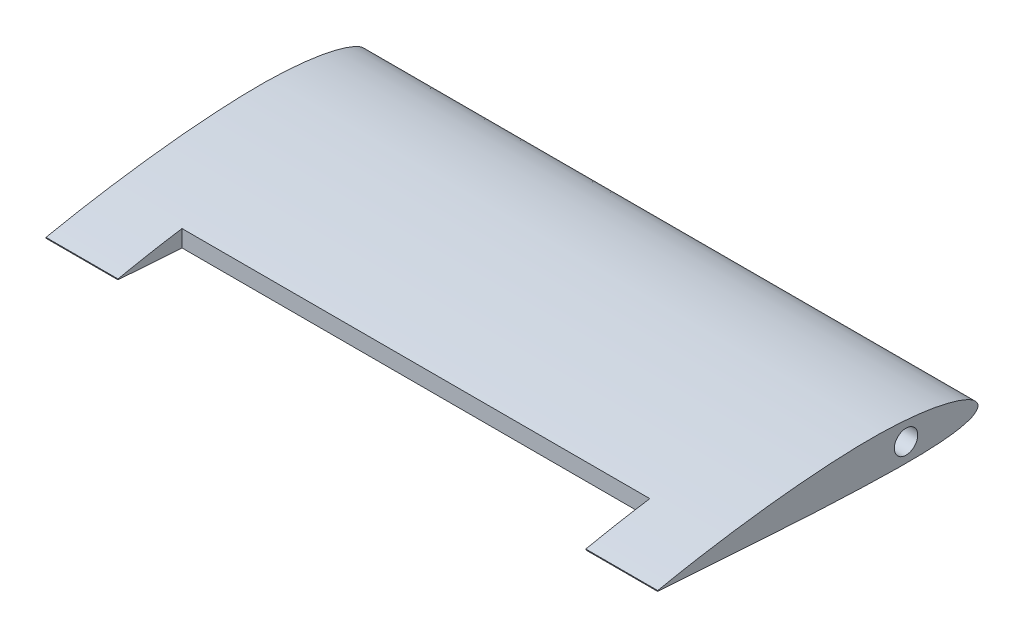
SolidWorks part; units mm, degrees
ref_plane "Front Plane" through (0, 0, 0) normal (0, 0, 1) x (1, 0, 0)
ref_plane "Top Plane" through (0, 0, 0) normal (0, 1, 0) x (1, 0, 0)
ref_plane "Right Plane" through (0, 0, 0) normal (1, 0, 0) x (0, 0, -1)
sketch "Sketch4" plane through (0, 0, 0) normal (0, 0, 1) x (1, 0, 0)
  line L0 (-30.3109, 17.5) -> (30.3109, 17.5)
  arc A1 (30.3109, 17.5) -> (-30.3109, 17.5) centre (0, 0) ccw
  dimension "D1" = 35
  dimension "D2" = 17.5
extrude "Exterior" add sketch "Sketch4" along normal blind 89 contours L0 A1
sketch "Sketch5" plane through (0, 0, 0) normal (0, 0, -1) x (-1, 0, 0)
  line L0 (30.3109, 17.5) -> (-30.3109, 17.5) construction
  line L1 (23.1247, 17.5) -> (-23.1247, 17.5)
  arc A0 (23.1247, 17.5) -> (-23.1247, 17.5) centre (0, 0) ccw
  dimension "D1" = 58
extrude "Boss-Extrude1" add sketch "Sketch5" along normal blind 15
curve "Curve3"
  spline degree 3 poles (0, 1.3, 1000) (0, 4.7133, 983.3426) (0, 11.531, 950.0715) (0, 24.0186, 883.4722) (0, 37.8548, 800.1781) (0, 52.175, 700.1592) (0, 64.1175, 600.1567) (0, 72.8619, 500.1109) (0, 78.7837, 400.0878) (0, 79.786, 316.6355) (0, 77.0249, 249.9395) (0, 72.979, 199.8766) (0, 66.5721, 149.7505) (0, 58.6825, 108.0331) (0, 49.7566, 74.7751) (0, 41.6416, 49.5609) (0, 32.1864, 28.1982) (0, 20.723, 9.771) (0, 0.8988, -6.2982) (0, -16.5264, 10.3934) (0, -24.4739, 28.476) (0, -30.5108, 49.7447) (0, -34.8393, 74.8759) (0, -38.5332, 108.2669) (0, -41.3764, 149.947) (0, -42.5163, 199.9941) (0, -42.3574, 250.0055) (0, -40.8857, 316.6783) (0, -38.2375, 400.0272) (0, -33.6287, 500.0334) (0, -27.6385, 600.0106) (0, -21.4122, 700.0048) (0, -15.1098, 800.0161) (0, -9.3053, 883.3314) (0, -4.8282, 950.0042) (0, -2.4761, 983.334) (0, -1.3, 1000) knots 0 0 0 0 0.025012 0.049959 0.099673 0.149206 0.198581 0.247805 0.296917 0.345953 0.370492 0.395091 0.419815 0.444799 0.45749 0.470406 0.483879 0.491264 0.503459 0.513609 0.520451 0.533235 0.545691 0.558032 0.582609 0.607135 0.631652 0.656174 0.705234 0.75432 0.803437 0.852566 0.901701 0.950849 0.975423 1 1 1 1
sketch "Sketch7" plane through (0, 0, 0) normal (1, 0, 0) x (0, 0, -1)
  line L0 (-89, 21.3887) -> (-89, 21.1573)
  line L1 (-89, 21.273) -> (0, 21.3903) construction
  line L2 (0, 21.3903) -> (-0.0573, 64.8516) construction
  line L7 (-89, 17.5) -> (0, 17.5) construction
  line L9 (0, 17.5) -> (0, 29) construction
  spline S1 degree 3 poles (-89, 21.3887) (-87.5176, 21.6924) (-84.5567, 22.2992) (-78.6297, 23.4105) (-71.2171, 24.6418) (-62.316, 25.9162) (-53.4164, 26.979) (-44.5129, 27.7573) (-35.6114, 28.2842) (-28.1847, 28.3735) (-22.2492, 28.1277) (-17.7939, 27.7677) (-13.3329, 27.1975) (-9.6203, 26.4954) (-6.6606, 25.701) (-4.4167, 24.9788) (-2.5155, 24.1374) (-0.8756, 23.1172) (0.5545, 21.353) (-0.931, 19.8022) (-2.5402, 19.095) (-4.433, 18.5577) (-6.6696, 18.1725) (-9.6412, 17.8438) (-13.3504, 17.5907) (-17.8043, 17.4893) (-22.255, 17.5034) (-28.1885, 17.6344) (-35.606, 17.8701) (-44.506, 18.2802) (-53.4034, 18.8133) (-62.3022, 19.3674) (-71.2026, 19.9283) (-78.6172, 20.4449) (-84.5507, 20.8433) (-87.5168, 21.0526) (-89, 21.1573) knots 0 0 0 0 0.025012 0.049959 0.099673 0.149206 0.198581 0.247805 0.296917 0.345953 0.370492 0.395091 0.419815 0.444799 0.45749 0.470406 0.483879 0.491264 0.503459 0.513609 0.520451 0.533235 0.545691 0.558032 0.582609 0.607135 0.631652 0.656174 0.705234 0.75432 0.803437 0.852566 0.901701 0.950849 0.975423 1 1 1 1
  dimension "D1" = 89
ref_plane "Plane1" through (80, 0, 0) normal (1, 0, 0) x (0, 0, -1)
ref_plane "Plane2" through (-80, 0, 0) normal (1, 0, 0) x (0, 0, -1)
sketch "Sketch8" plane through (80, 0, 0) normal (1, 0, 0) x (0, 0, -1)
  line L0 (-89, 21.3887) -> (-89, 21.1573)
  spline S0 degree 3 poles (-469.3669, 946.2185) (-209.3584, -26.81) (-147.9272, 10.417) (-78.6297, 23.4105) (-71.2171, 24.6418) (-62.316, 25.9162) (-53.4164, 26.979) (-44.5129, 27.7573) (-35.6114, 28.2842) (-28.1847, 28.3735) (-22.2492, 28.1277) (-17.7939, 27.7677) (-13.3329, 27.1975) (-9.6203, 26.4954) (-6.6606, 25.701) (-4.4167, 24.9788) (-2.5155, 24.1374) (-0.8756, 23.1172) (0.5545, 21.353) (-0.931, 19.8022) (-2.5402, 19.095) (-4.433, 18.5577) (-6.6696, 18.1725) (-9.6412, 17.8438) (-13.3504, 17.5907) (-17.8043, 17.4893) (-22.255, 17.5034) (-28.1885, 17.6344) (-35.606, 17.8701) (-44.506, 18.2802) (-53.4034, 18.8133) (-62.3022, 19.3674) (-71.2026, 19.9283) (-78.6172, 20.4449) (-191.4759, 28.0234) (-300.415, 49.2551) (-474.7288, -901.4445) knots -1.065698 -1.065698 -1.065698 -1.065698 0.025012 0.049959 0.099673 0.149206 0.198581 0.247805 0.296917 0.345953 0.370492 0.395091 0.419815 0.444799 0.45749 0.470406 0.483879 0.491264 0.503459 0.513609 0.520451 0.533235 0.545691 0.558032 0.582609 0.607135 0.631652 0.656174 0.705234 0.75432 0.803437 0.852566 0.901701 0.950849 0.975423 2.771414 2.771414 2.771414 2.771414 only from (-89, 21.3887) to (-89, 21.1573) construction
  spline S1 degree 3 poles (-89, 21.3887) (-87.5176, 21.6924) (-84.5567, 22.2992) (-78.6297, 23.4105) (-71.2171, 24.6418) (-62.316, 25.9162) (-53.4164, 26.979) (-44.5129, 27.7573) (-35.6114, 28.2842) (-28.1847, 28.3735) (-22.2492, 28.1277) (-17.7939, 27.7677) (-13.3329, 27.1975) (-9.6203, 26.4954) (-6.6606, 25.701) (-4.4167, 24.9788) (-2.5155, 24.1374) (-0.8756, 23.1172) (0.5545, 21.353) (-0.931, 19.8022) (-2.5402, 19.095) (-4.433, 18.5577) (-6.6696, 18.1725) (-9.6412, 17.8438) (-13.3504, 17.5907) (-17.8043, 17.4893) (-22.255, 17.5034) (-28.1885, 17.6344) (-35.606, 17.8701) (-44.506, 18.2802) (-53.4034, 18.8133) (-62.3022, 19.3674) (-71.2026, 19.9283) (-78.6172, 20.4449) (-84.5507, 20.8433) (-87.5168, 21.0526) (-89, 21.1573) knots 0 0 0 0 0.025012 0.049959 0.099673 0.149206 0.198581 0.247805 0.296917 0.345953 0.370492 0.395091 0.419815 0.444799 0.45749 0.470406 0.483879 0.491264 0.503459 0.513609 0.520451 0.533235 0.545691 0.558032 0.582609 0.607135 0.631652 0.656174 0.705234 0.75432 0.803437 0.852566 0.901701 0.950849 0.975423 1 1 1 1
sketch "Sketch9" plane through (-80, 0, 0) normal (1, 0, 0) x (0, 0, -1)
  line L0 (-89, 21.3887) -> (-89, 21.1573)
  spline S0 degree 3 poles (-469.3669, 946.2185) (-209.3584, -26.81) (-147.9272, 10.417) (-78.6297, 23.4105) (-71.2171, 24.6418) (-62.316, 25.9162) (-53.4164, 26.979) (-44.5129, 27.7573) (-35.6114, 28.2842) (-28.1847, 28.3735) (-22.2492, 28.1277) (-17.7939, 27.7677) (-13.3329, 27.1975) (-9.6203, 26.4954) (-6.6606, 25.701) (-4.4167, 24.9788) (-2.5155, 24.1374) (-0.8756, 23.1172) (0.5545, 21.353) (-0.931, 19.8022) (-2.5402, 19.095) (-4.433, 18.5577) (-6.6696, 18.1725) (-9.6412, 17.8438) (-13.3504, 17.5907) (-17.8043, 17.4893) (-22.255, 17.5034) (-28.1885, 17.6344) (-35.606, 17.8701) (-44.506, 18.2802) (-53.4034, 18.8133) (-62.3022, 19.3674) (-71.2026, 19.9283) (-78.6172, 20.4449) (-191.4759, 28.0234) (-300.415, 49.2551) (-474.7288, -901.4445) knots -1.065698 -1.065698 -1.065698 -1.065698 0.025012 0.049959 0.099673 0.149206 0.198581 0.247805 0.296917 0.345953 0.370492 0.395091 0.419815 0.444799 0.45749 0.470406 0.483879 0.491264 0.503459 0.513609 0.520451 0.533235 0.545691 0.558032 0.582609 0.607135 0.631652 0.656174 0.705234 0.75432 0.803437 0.852566 0.901701 0.950849 0.975423 2.771414 2.771414 2.771414 2.771414 only from (-89, 21.3887) to (-89, 21.1573) construction
  spline S1 degree 3 poles (-89, 21.3887) (-87.5176, 21.6924) (-84.5567, 22.2992) (-78.6297, 23.4105) (-71.2171, 24.6418) (-62.316, 25.9162) (-53.4164, 26.979) (-44.5129, 27.7573) (-35.6114, 28.2842) (-28.1847, 28.3735) (-22.2492, 28.1277) (-17.7939, 27.7677) (-13.3329, 27.1975) (-9.6203, 26.4954) (-6.6606, 25.701) (-4.4167, 24.9788) (-2.5155, 24.1374) (-0.8756, 23.1172) (0.5545, 21.353) (-0.931, 19.8022) (-2.5402, 19.095) (-4.433, 18.5577) (-6.6696, 18.1725) (-9.6412, 17.8438) (-13.3504, 17.5907) (-17.8043, 17.4893) (-22.255, 17.5034) (-28.1885, 17.6344) (-35.606, 17.8701) (-44.506, 18.2802) (-53.4034, 18.8133) (-62.3022, 19.3674) (-71.2026, 19.9283) (-78.6172, 20.4449) (-84.5507, 20.8433) (-87.5168, 21.0526) (-89, 21.1573) knots 0 0 0 0 0.025012 0.049959 0.099673 0.149206 0.198581 0.247805 0.296917 0.345953 0.370492 0.395091 0.419815 0.444799 0.45749 0.470406 0.483879 0.491264 0.503459 0.513609 0.520451 0.533235 0.545691 0.558032 0.582609 0.607135 0.631652 0.656174 0.705234 0.75432 0.803437 0.852566 0.901701 0.950849 0.975423 1 1 1 1
loft "Loft9" add profiles "Sketch8", "Sketch9"
sketch "Sketch12" plane through (80, 0, 0) normal (1, 0, 0) x (0, 0, -1)
  line L0 (-89, 21.3887) -> (-89, 21.1573) construction
  line L1 (-89, 21.3887) -> (-89, 21.1573)
  line L2 (-89, 21.3887) -> (-97.2409, 26.9065)
  line L3 (-97.2409, 26.9065) -> (-90.2923, 42.7722)
  line L4 (-90.2923, 42.7722) -> (-30.1138, 44.0233)
  line L5 (-30.1138, 44.0233) -> (6.4186, 38.5184)
  line L6 (6.4186, 38.5184) -> (-0.0099, 28.9175)
  line L7 (0, 21.3903) -> (-0.0573, 64.8516) construction
  line L8 (-0.0099, 28.9175) -> (-30.6202, 28.3197)
  spline S0 degree 3 poles (-713.3875, 1915.884) (-239.966, -47.1163) (-164.6221, 7.2867) (-78.6297, 23.4105) (-71.2171, 24.6418) (-62.316, 25.9162) (-53.4164, 26.979) (-44.5129, 27.7573) (-35.6114, 28.2842) (-28.1847, 28.3735) (-22.2492, 28.1277) (-17.7939, 27.7677) (-13.3329, 27.1975) (-9.6203, 26.4954) (-6.6606, 25.701) (-4.4167, 24.9788) (-2.5155, 24.1374) (-0.8756, 23.1172) (0.5545, 21.353) (-0.931, 19.8022) (-2.5402, 19.095) (-4.433, 18.5577) (-6.6696, 18.1725) (-9.6412, 17.8438) (-13.3504, 17.5907) (-17.8043, 17.4893) (-22.255, 17.5034) (-28.1885, 17.6344) (-35.606, 17.8701) (-44.506, 18.2802) (-53.4034, 18.8133) (-62.3022, 19.3674) (-71.2026, 19.9283) (-78.6172, 20.4449) (-220.4152, 29.9667) (-357.7257, 61.3982) (-629.9057, -1889.2617) knots -1.346455 -1.346455 -1.346455 -1.346455 0.025012 0.049959 0.099673 0.149206 0.198581 0.247805 0.296917 0.345953 0.370492 0.395091 0.419815 0.444799 0.45749 0.470406 0.483879 0.491264 0.503459 0.513609 0.520451 0.533235 0.545691 0.558032 0.582609 0.607135 0.631652 0.656174 0.705234 0.75432 0.803437 0.852566 0.901701 0.950849 0.975423 3.250848 3.250848 3.250848 3.250848 only from (-89, 21.3887) to (-89, 21.1573) construction
  spline S1 degree 3 poles (-89, 21.3887) (-87.5176, 21.6924) (-84.5567, 22.2992) (-78.6297, 23.4105) (-71.2171, 24.6418) (-62.316, 25.9162) (-53.4164, 26.979) (-44.5129, 27.7573) (-36.9147, 28.2071) (-32.2817, 28.3107) (-30.6202, 28.3197) knots 0 0 0 0 0.025012 0.049959 0.099673 0.149206 0.198581 0.247805 0.296917 0.324377 0.324377 0.324377 0.324377
  spline S2 degree 3 poles (-89, 21.3887) (-87.5176, 21.6924) (-84.5567, 22.2992) (-78.6297, 23.4105) (-71.2171, 24.6418) (-62.316, 25.9162) (-53.4164, 26.979) (-44.5129, 27.7573) (-36.9147, 28.2071) (-32.2817, 28.3107) (-30.6202, 28.3197) knots 0 0 0 0 0.025012 0.049959 0.099673 0.149206 0.198581 0.247805 0.296917 0.324377 0.324377 0.324377 0.324377
extrude "Cut-Extrude1" cut sketch "Sketch12" against normal through all
ref_plane "Plane3" through (0, 30, 0) normal (0, 1, 0) x (1, 0, 0)
sketch "Sketch17" plane through (-80, 0, 0) normal (-1, 0, 0) x (0, 0, 1)
  line L0 (89, 21.3887) -> (89, 21.1573) construction
  line L1 (89, 21.3887) -> (89, 21.1573)
  spline S0 degree 3 poles (713.3875, 1915.884) (239.966, -47.1163) (164.6221, 7.2867) (78.6297, 23.4105) (71.2171, 24.6418) (62.316, 25.9162) (53.4164, 26.979) (44.5129, 27.7573) (35.6114, 28.2842) (28.1847, 28.3735) (22.2492, 28.1277) (17.7939, 27.7677) (13.3329, 27.1975) (9.6203, 26.4954) (6.6606, 25.701) (4.4167, 24.9788) (2.5155, 24.1374) (0.8756, 23.1172) (-0.5545, 21.353) (0.931, 19.8022) (2.5402, 19.095) (4.433, 18.5577) (6.6696, 18.1725) (9.6412, 17.8438) (13.3504, 17.5907) (17.8043, 17.4893) (22.255, 17.5034) (28.1885, 17.6344) (35.606, 17.8701) (44.506, 18.2802) (53.4034, 18.8133) (62.3022, 19.3674) (71.2026, 19.9283) (78.6172, 20.4449) (220.4152, 29.9667) (357.7257, 61.3982) (629.9057, -1889.2617) knots -1.346455 -1.346455 -1.346455 -1.346455 0.025012 0.049959 0.099673 0.149206 0.198581 0.247805 0.296917 0.345953 0.370492 0.395091 0.419815 0.444799 0.45749 0.470406 0.483879 0.491264 0.503459 0.513609 0.520451 0.533235 0.545691 0.558032 0.582609 0.607135 0.631652 0.656174 0.705234 0.75432 0.803437 0.852566 0.901701 0.950849 0.975423 3.250848 3.250848 3.250848 3.250848 only from (89, 21.3887) to (89, 21.1573) construction
  spline S1 degree 3 poles (89, 21.3887) (87.5176, 21.6924) (84.5567, 22.2992) (78.6297, 23.4105) (71.2171, 24.6418) (62.316, 25.9162) (53.4164, 26.979) (44.5129, 27.7573) (35.6114, 28.2842) (28.1847, 28.3735) (22.2492, 28.1277) (17.7939, 27.7677) (13.3329, 27.1975) (9.6203, 26.4954) (6.6606, 25.701) (4.4167, 24.9788) (2.5155, 24.1374) (0.8756, 23.1172) (-0.5545, 21.353) (0.931, 19.8022) (2.5402, 19.095) (4.433, 18.5577) (6.6696, 18.1725) (9.6412, 17.8438) (13.3504, 17.5907) (17.8043, 17.4893) (22.255, 17.5034) (28.1885, 17.6344) (35.606, 17.8701) (44.506, 18.2802) (53.4034, 18.8133) (62.3022, 19.3674) (71.2026, 19.9283) (78.6172, 20.4449) (84.5507, 20.8433) (87.5168, 21.0526) (89, 21.1573) knots 0 0 0 0 0.025012 0.049959 0.099673 0.149206 0.198581 0.247805 0.296917 0.345953 0.370492 0.395091 0.419815 0.444799 0.45749 0.470406 0.483879 0.491264 0.503459 0.513609 0.520451 0.533235 0.545691 0.558032 0.582609 0.607135 0.631652 0.656174 0.705234 0.75432 0.803437 0.852566 0.901701 0.950849 0.975423 1 1 1 1
extrude "Boss-Extrude2" add sketch "Sketch17" along normal blind 170
ref_plane "Plane5" through (-165, 0, 0) normal (1, 0, 0) x (0, 0, -1)
ref_plane "Plane6" through (-80, 0, 0) normal (1, 0, 0) x (0, 0, -1)
sketch "Sketch18" plane through (-80, 0, 0) normal (1, 0, 0) x (0, 0, -1)
  line L0 (-99.867, 5.7154) -> (-104.3901, 63.3258)
  line L1 (-104.3901, 63.3258) -> (31.8989, 60.8261)
  line L2 (31.8989, 60.8261) -> (39.2788, -3.2119)
  line L3 (39.2788, -3.2119) -> (-99.867, 5.7154)
extrude "Cut-Extrude6" cut sketch "Sketch18" along normal through all
sketch "Sketch13" plane through (-80, 0, 0) normal (-1, 0, 0) x (0, 0, 1)
  line L0 (20, 17.5005) -> (20, 27.9379) construction
  circle A0 centre (20, 22.7192) radius 3.25
  spline S0 degree 3 poles (89, 21.3887) (87.5176, 21.6924) (84.5567, 22.2992) (78.6297, 23.4105) (71.2171, 24.6418) (62.316, 25.9162) (53.4164, 26.979) (44.5129, 27.7573) (35.6114, 28.2842) (28.1847, 28.3735) (22.2492, 28.1277) (17.7939, 27.7677) (13.3329, 27.1975) (9.6203, 26.4954) (6.6606, 25.701) (4.4167, 24.9788) (2.5155, 24.1374) (0.8756, 23.1172) (-0.5545, 21.353) (0.931, 19.8022) (2.5402, 19.095) (4.433, 18.5577) (6.6696, 18.1725) (9.6412, 17.8438) (13.3504, 17.5907) (17.8043, 17.4893) (22.255, 17.5034) (28.1885, 17.6344) (35.606, 17.8701) (44.506, 18.2802) (53.4034, 18.8133) (62.3022, 19.3674) (71.2026, 19.9283) (78.6172, 20.4449) (84.5507, 20.8433) (87.5168, 21.0526) (89, 21.1573) knots 0 0 0 0 0.025012 0.049959 0.099673 0.149206 0.198581 0.247805 0.296917 0.345953 0.370492 0.395091 0.419815 0.444799 0.45749 0.470406 0.483879 0.491264 0.503459 0.513609 0.520451 0.533235 0.545691 0.558032 0.582609 0.607135 0.631652 0.656174 0.705234 0.75432 0.803437 0.852566 0.901701 0.950849 0.975423 1 1 1 1 construction
  point P8 (20, 22.7192)
  dimension "D1" = 6.5
  dimension "D2" = 20
extrude "Cut-Extrude2" cut sketch "Sketch13" against normal through all and the other way through all
sketch "Sketch19" plane through (0, 0, 0) normal (0, 1, 0) x (1, 0, 0)
  line L0 (-183.5, -62.5) -> (-183.5, -26.5)
  line L1 (-183.5, -26.5) -> (-146.5, -26.5)
  line L2 (-146.5, -26.5) -> (-146.5, -62.5)
  line L3 (-146.5, -62.5) -> (-183.5, -62.5)
  line L4 (-165, -9.0116) -> (-165, 9.0116) construction
  line L6 (-80, 0) -> (-250, 0) construction
  point P6 (-165, -62.5)
  point P7 (-183.5, -44.5)
  dimension "D1" = 36
  dimension "D2" = 37
  dimension "D3" = 44.5
extrude "Cut-Extrude7" cut sketch "Sketch19" along normal blind 23
sketch "Sketch20" plane through (0, 30, 0) normal (0, 1, 0) x (1, 0, 0)
  line L0 (-230, -89) -> (-230, -71.2)
  line L1 (-230, -71.2) -> (-100, -71.2)
  line L2 (-100, -71.2) -> (-100, -89)
  line L3 (-250, -89) -> (-80, -89) construction
  line L4 (-100, -89) -> (-230, -89)
  line L5 (-250, 0) -> (-250, -89) construction
  line L6 (-80, -89) -> (-80, 0) construction
  dimension "D1" = 20
  dimension "D2" = 20
  dimension "D3" = 17.8
extrude "Cut-Extrude8" cut sketch "Sketch20" against normal through all
equation "\"fuse_diam\"= 0.07"
equation "\"fuse_rad\"= 0.035"
equation "\"battery_length\"= 0.076"
equation "\"battery_width\"= 0.034"
equation "\"battery_height\"= 0.051"
equation "\"bat_bay_length\"= 0.096"
equation "\"shell\"= 0.002"
equation "\"D1@Exterior\"=\"chord_length\""
equation "\"wing_shelf\"= 0.0175"
equation "\"chord_length\"= 0.089"
equation "\"tail_length\"= 0.26532000000000006"
equation "\"tail_diam\"= 0.035"
equation "\"connector\"= 0.06633000000000001"
equation "\"D2@Sketch4\"=\"wing_shelf\""
equation "\"D1@Sketch4\"=\"fuse_rad\""
equation "\"D1@Sketch5\"=\"fuse_diam\"-0.012"
equation "\"D1@Sketch7\"=\"chord_length\""
equation "\"D3@Sketch19\"=\"chord_length\"/2"
equation "\"D3@Sketch20\"=\"chord_length\"/5"
